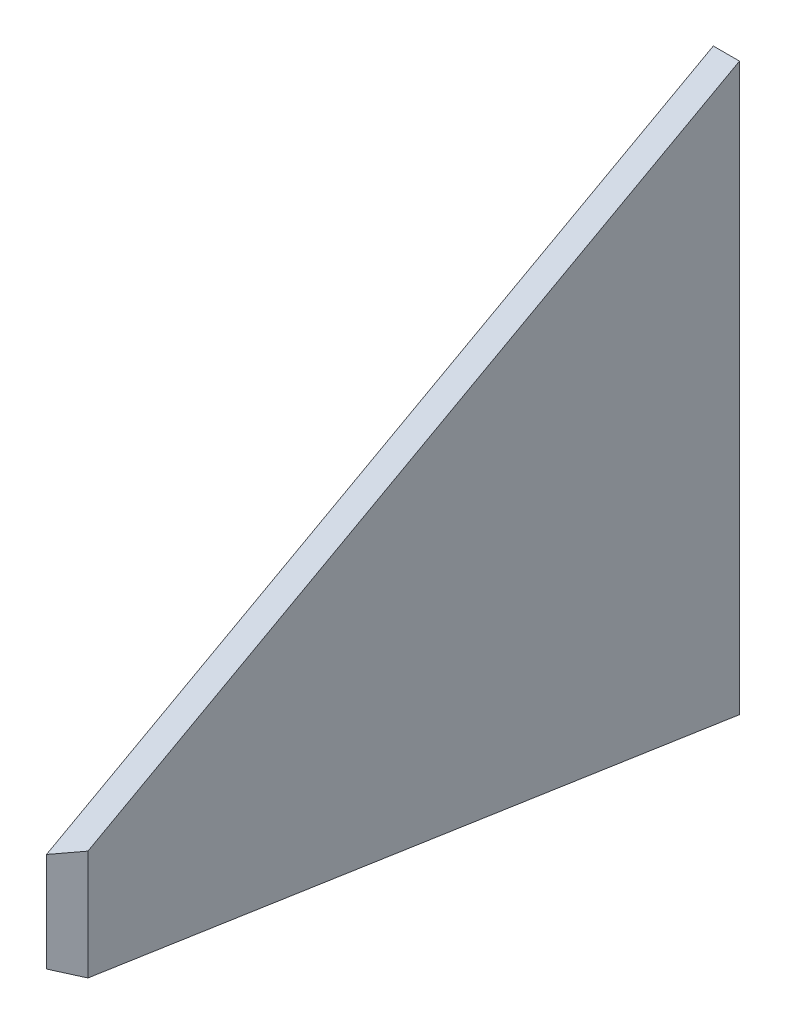
SolidWorks part; units mm, degrees
ref_plane "Front Plane" through (0, 0, 0) normal (0, 0, 1) x (1, 0, 0)
ref_plane "Top Plane" through (0, 0, 0) normal (0, 1, 0) x (1, 0, 0)
ref_plane "Right Plane" through (0, 0, 0) normal (1, 0, 0) x (0, 0, -1)
sketch "Sketch2" plane through (0, 0, 0) normal (0, 1, 0) x (1, 0, 0)
  line L0 (-57.15, 0) -> (224.536, 0)
  line L1 (224.536, 0) -> (-24.3577, -196.7539)
  line L2 (-24.3577, -196.7539) -> (-57.15, 0)
  line L3 (0, 0) -> (0, -152.4) construction
  line L4 (-31.75, -152.4) -> (31.75, -152.4) construction
  point P2 (0, 0)
  dimension "D1" = 281.686
  dimension "D2" = 57.15
  dimension "D3" = 63.5
  dimension "D4" = 152.4
extrude "Boss-Extrude1" add sketch "Sketch2" along normal blind 152.4
ref_plane "Plane1" through (-63.5, 0, 0) normal (1, 0, 0) x (0, 0, -1)
sketch "Sketch3" plane through (-63.5, 0, 0) normal (1, 0, 0) x (0, 0, -1)
  line L0 (0, 76.2) -> (-152.4, 76.2) construction
  line L1 (0, 152.4) -> (0, 0) construction
  line L2 (-152.4, 44.45) -> (-152.4, 107.95) construction
  line L3 (0, 152.4) -> (-152.4, 107.95)
  line L4 (0, 0) -> (-152.4, 44.45)
  line L5 (-152.4, 107.95) -> (-261.2571, 76.2)
  line L6 (-152.4, 44.45) -> (-261.2571, 76.2)
  line L7 (0, 152.4) -> (0, 0)
  point P7 (-152.4, 76.2)
  dimension "D1" = 152.4
  dimension "D2" = 63.5
extrude "Cut-Extrude2" cut sketch "Sketch3" along normal through all flip side to cut
shell "Shell1" thickness 6.35
sketch "Sketch4" plane through (-63.5, 0, 0) normal (1, 0, 0) x (0, 0, -1)
  line L1 (0, 152.4) -> (0, 145.7854)
  line L2 (0, 145.7854) -> (-196.7539, 88.3989)
  line L4 (-196.7539, 64.0011) -> (0, 6.6146)
  line L5 (0, 152.4) -> (-196.7539, 95.0134)
  line L7 (-196.7539, 57.3866) -> (0, 0)
  line L8 (-196.7539, 95.0134) -> (-196.7539, 57.3866) construction
  line L9 (-196.7539, 95.0134) -> (-196.7539, 88.3989)
  line L10 (-196.7539, 64.0011) -> (-196.7539, 57.3866)
  line L11 (0, 152.4) -> (0, 0) construction
  line L12 (0, 0) -> (0, 6.6146)
extrude "Cut-Extrude3" cut sketch "Sketch4" along normal through all
ref_plane "Plane2" through (0, 149.86, 0) normal (0, 1, 0) x (1, 0, 0)
sketch "Sketch5" plane through (0, 149.86, 0) normal (0, 1, 0) x (1, 0, 0)
  line L0 (-19.8615, -185.1052) -> (-18.6695, -192.2573)
  line L1 (-24.3577, -196.7539) -> (224.536, 0) construction
  line L2 (-19.8615, -185.1052) -> (-50.7124, 0) construction
  line L3 (-18.6695, -192.2573) -> (344.3171, -192.2573)
  line L4 (344.3171, -192.2573) -> (317.8797, 72.8643)
  line L5 (317.8797, 72.8643) -> (-35.1367, 43.3166)
  line L6 (-35.1367, 43.3166) -> (-19.8615, -185.1052)
extrude "Cut-Extrude4" cut sketch "Sketch5" against normal through all
